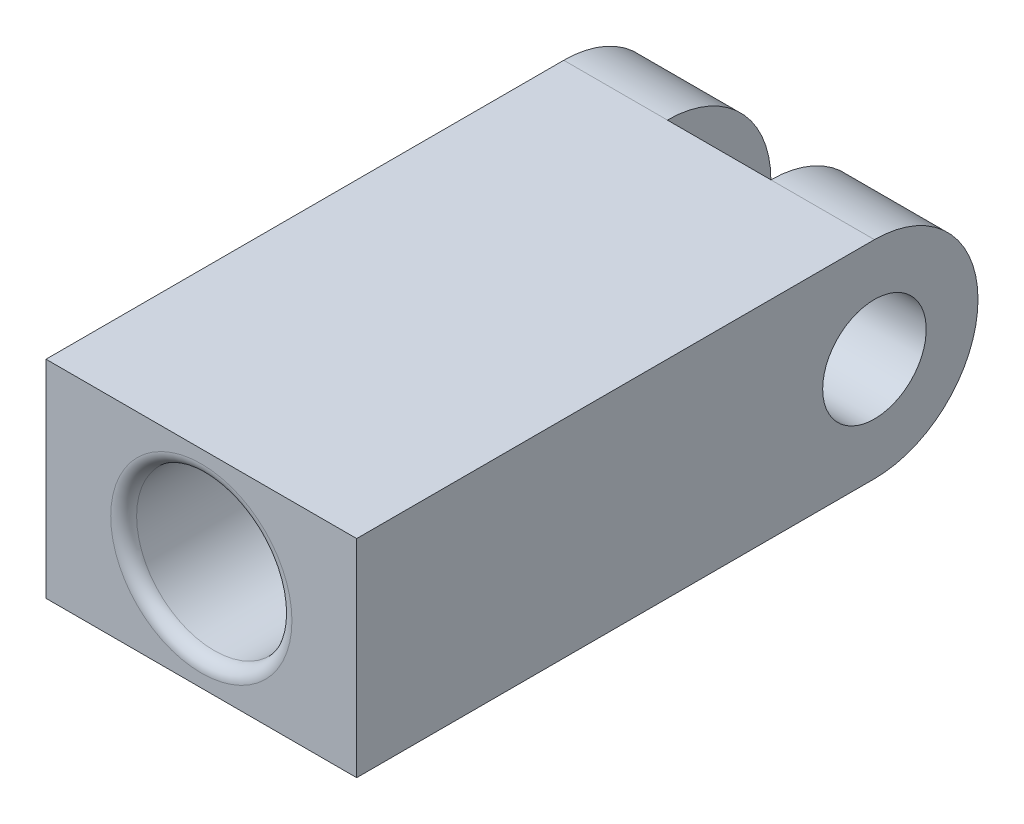
SolidWorks part; units mm, degrees
ref_plane "정면" through (0, 0, 0) normal (0, 0, 1) x (1, 0, 0)
ref_plane "윗면" through (0, 0, 0) normal (0, 1, 0) x (1, 0, 0)
ref_plane "우측면" through (0, 0, 0) normal (1, 0, 0) x (0, 0, -1)
sketch "스케치1" plane through (0, 0, 0) normal (0, 0, 1) x (1, 0, 0)
  line L1 (50, -15) -> (-10, -15)
  line L2 (50, -15) -> (50, 25)
  line L3 (50, 25) -> (-10, 25)
  line L4 (-10, -15) -> (-10, 25)
  line L5 (50, -15) -> (-10, 25) construction
  line L6 (50, 25) -> (-10, -15) construction
  dimension "D1" = 40
  dimension "D2" = 60
extrude "보스-돌출1" add sketch "스케치1" along normal blind 100
sketch "스케치6" plane through (50, 0, 0) normal (1, 0, 0) x (0, 0, -1)
  line L0 (0, -15) -> (0, 25) construction
  circle A0 centre (0, 5) radius 20
extrude "보스-돌출2" add sketch "스케치6" against normal blind 20
sketch "스케치7" plane through (-10, 0, 0) normal (-1, 0, 0) x (0, 0, 1)
  line L0 (0, 25) -> (0, -15) construction
  circle A0 centre (0, 5) radius 20
extrude "보스-돌출3" add sketch "스케치7" against normal blind 20
sketch "스케치8" plane through (-10, 0, 0) normal (-1, 0, 0) x (0, 0, 1)
  circle A0 centre (0, 5) radius 10
  dimension "D1" = 20
extrude "컷-돌출1" cut sketch "스케치8" against normal through all both and the other way through all
ref_plane "평면1" through (0, 0, 0) normal (0, 0, 1) x (1, 0, 0)
sketch "스케치9" plane through (30, 0, 0) normal (-1, 0, 0) x (0, 0, 1)
  circle A0 centre (0, 5) radius 20
  dimension "D1" = 40
extrude "컷-돌출2" cut sketch "스케치9" along normal blind 20
sketch "스케치10" plane through (0, 0, 100) normal (0, 0, 1) x (1, 0, 0)
  line L0 (-10, 25) -> (7.5192, 13.3205)
  line L1 (50, 25) -> (32.4808, 13.3205)
  line L2 (32.4808, -3.3205) -> (50, -15)
  line L3 (7.5192, -3.3205) -> (-10, -15)
  circle A0 centre (20, 5) radius 15
  dimension "D1" = 30
extrude "컷-돌출3" cut sketch "스케치10" against normal blind 30 contours A0
fillet "필렛2" radius 2.5 1 edges at (35, 5, 100)
